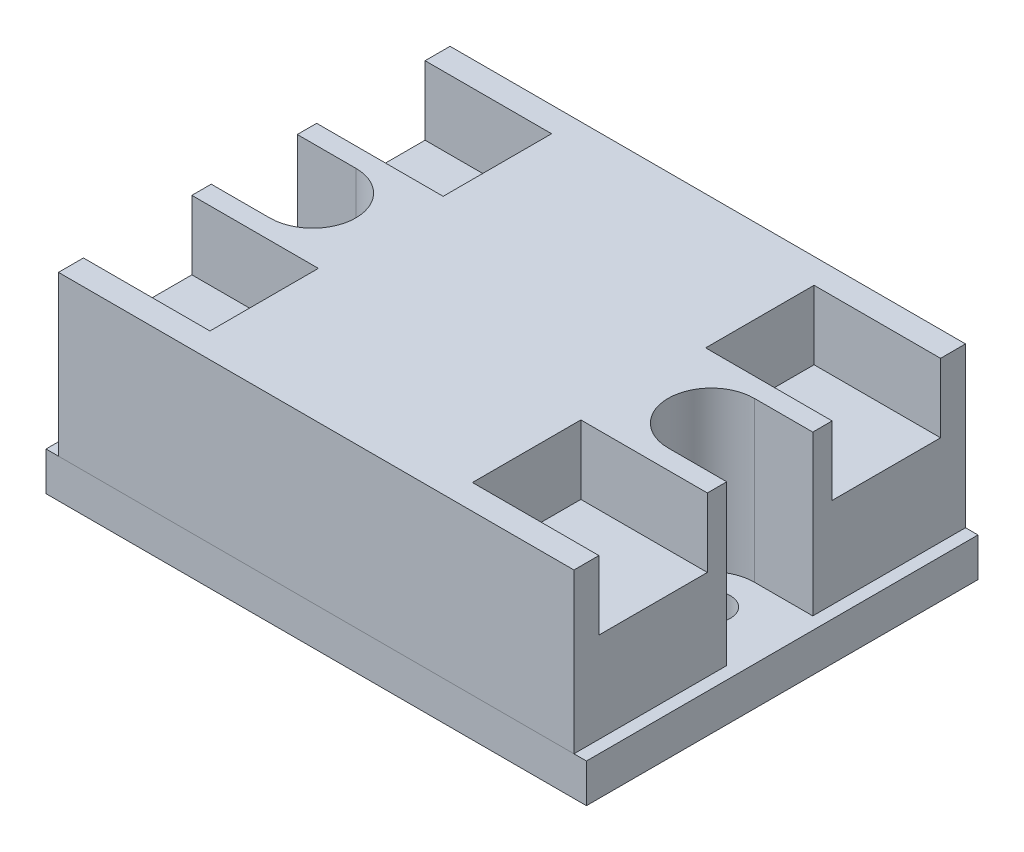
SolidWorks part; units mm, degrees
ref_plane "Plan de face" through (0, 0, 0) normal (0, 0, 1) x (1, 0, 0)
ref_plane "Plan de dessus" through (0, 0, 0) normal (0, 1, 0) x (1, 0, 0)
ref_plane "Plan de droite" through (0, 0, 0) normal (1, 0, 0) x (0, 0, -1)
sketch "Esquisse1" plane through (0, 0, 0) normal (0, 1, 0) x (1, 0, 0)
  line L0 (-31.4, -22.75) -> (31.4, 22.75) construction
  line L1 (-31.4, 22.75) -> (31.4, 22.75)
  line L2 (-31.4, 22.75) -> (-31.4, -22.75)
  line L3 (-31.4, -22.75) -> (31.4, -22.75)
  line L4 (31.4, 22.75) -> (31.4, -22.75)
  point P4 (0, 0)
  dimension "D1" = 62.8
  dimension "D2" = 45.5
extrude "Boss.-Extru.1" add sketch "Esquisse1" along normal blind 4.5
sketch "Esquisse2" plane through (0, 4.5, 0) normal (0, 1, 0) x (1, 0, 0)
  line L0 (31.4, 22.75) -> (-31.4, 22.75) construction
  line L1 (-29.95, 22.75) -> (29.95, 22.75)
  line L2 (-29.95, 22.75) -> (-29.95, -22.75)
  line L3 (-29.95, -22.75) -> (29.95, -22.75)
  line L4 (29.95, 22.75) -> (29.95, -22.75)
  line L6 (0, 0) -> (0, 22.75) construction
  line L7 (-31.4, -22.75) -> (31.4, -22.75) construction
  point P6 (29.95, -18.6567)
  point P7 (29.95, -22.75)
  dimension "D1" = 59.9
extrude "Boss.-Extru.2" add sketch "Esquisse2" along normal blind 18.5 separate body
sketch "Esquisse3" plane through (0, 23, 0) normal (0, 1, 0) x (1, 0, 0)
  line L0 (36.75, 0) -> (23.15, 0) construction
  line L1 (29.95, -22.75) -> (29.95, 22.75) construction
  line L2 (36.75, -5) -> (23.15, -5)
  line L3 (36.75, 5) -> (23.15, 5)
  line L4 (0, 0) -> (0, 4.3519) construction
  line L5 (-36.75, 0) -> (-23.15, 0) construction
  line L6 (-36.75, -5) -> (-23.15, -5)
  line L7 (-36.75, 5) -> (-23.15, 5)
  arc A0 (36.75, -5) -> (36.75, 5) centre (36.75, 0) ccw
  arc A1 (23.15, 5) -> (23.15, -5) centre (23.15, 0) ccw
  arc A2 (-36.75, -5) -> (-36.75, 5) centre (-36.75, 0) cw
  arc A3 (-23.15, 5) -> (-23.15, -5) centre (-23.15, 0) cw
  point P5 (29.95, 0)
  point P10 (18.15, 0)
  point P15 (-29.95, 0)
  dimension "D1" = 10
  dimension "D2" = 11.8
extrude "Enlèv. mat.-Extru.1" cut sketch "Esquisse3" against normal up to surface (18.5 mm away) up to face at (0, 4.5, 0)
sketch "Esquisse4" plane through (0, 23, 0) normal (0, 1, 0) x (1, 0, 0)
  line L0 (29.95, 5) -> (29.95, 22.75) construction
  line L1 (29.95, 19.85) -> (15.25, 19.85)
  line L2 (29.95, 19.85) -> (29.95, 7.25)
  line L3 (29.95, 7.25) -> (15.25, 7.25)
  line L4 (15.25, 19.85) -> (15.25, 7.25)
  line L5 (0, 0) -> (0, 5.2993) construction
  line L6 (0, 0) -> (4.9019, 0) construction
  line L7 (-29.95, 7.25) -> (-15.25, 7.25)
  line L8 (-15.25, 19.85) -> (-15.25, 7.25)
  line L9 (-29.95, 19.85) -> (-15.25, 19.85)
  line L10 (-29.95, 19.85) -> (-29.95, 7.25)
  line L11 (29.95, -7.25) -> (15.25, -7.25)
  line L12 (15.25, -19.85) -> (15.25, -7.25)
  line L13 (29.95, -19.85) -> (15.25, -19.85)
  line L14 (29.95, -19.85) -> (29.95, -7.25)
  line L15 (-29.95, -19.85) -> (-29.95, -7.25)
  line L16 (-29.95, -19.85) -> (-15.25, -19.85)
  line L17 (-15.25, -19.85) -> (-15.25, -7.25)
  line L18 (-29.95, -7.25) -> (-15.25, -7.25)
  dimension "D1" = 12.6
  dimension "D2" = 14.7
  dimension "D3" = 14.5
extrude "Enlèv. mat.-Extru.2" cut sketch "Esquisse4" against normal blind 8
hole_wizard "Dégagement M41" positions "Esquisse5" profile "Esquisse6" hole size "M4" standard "ISO" end condition through all
sketch "Esquisse5" plane through (0, 4.5, 0) normal (0, 1, 0) x (1, 0, 0)
  line L0 (0, 0) -> (0, 4.3719) construction
  point P0 (23.15, 0)
  point P8 (23.15, 0)
  point P10 (-23.15, 0)
sketch "Esquisse6" plane through (23.15, 4.5, 0) normal (1, 0, 0) x (0, 0, 1)
  line L0 (0, 0) -> (0, 4.5)
  line L1 (0, 4.5) -> (2.25, 4.5)
  line L2 (2.25, 4.5) -> (2.25, 0)
  line L5 (2.25, 0) -> (0, 0)
  line L11 (0, -6.35) -> (0, 107.95) construction
  dimension "Diamètre du perçage jusqu'au prochain" = 4.5
  dimension "Profondeur du perçage jusqu'au prochain" = 4.5
